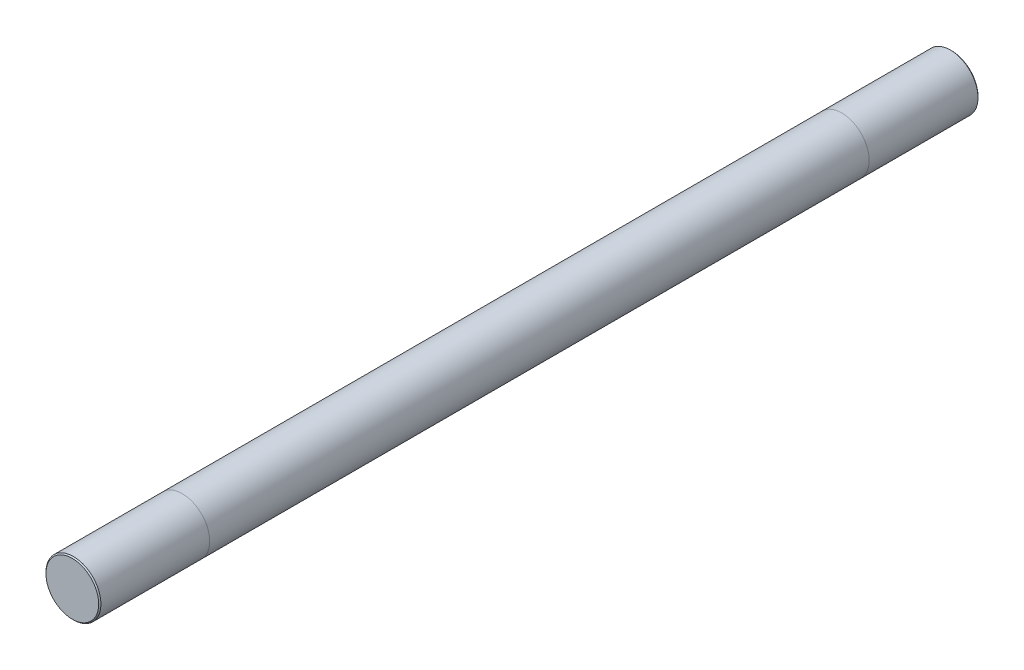
SolidWorks part; units mm, degrees
material "Plain Carbon Steel"
ref_plane "Front Plane" through (0, 0, 0) normal (0, 0, 1) x (1, 0, 0)
ref_plane "Top Plane" through (0, 0, 0) normal (0, 1, 0) x (1, 0, 0)
ref_plane "Right Plane" through (0, 0, 0) normal (1, 0, 0) x (0, 0, -1)
sketch "Sketch1" plane through (0, 0, 0) normal (0, 0, 1) x (1, 0, 0)
  circle A0 centre (0, 0) radius 3.175 construction
  dimension "Diameter" = 6.35
sketch "Sketch2" plane through (0, 0, 0) normal (1, 0, 0) x (0, 0, -1)
  line L0 (50.8, 0) -> (-50.8, 0) construction
  point P0 (-40.64, 0)
  point P3 (0, 0)
  point P4 (40.64, 0)
  point P6 (-35.56, 0)
  point P7 (35.56, 0)
  dimension "Length" = 101.6
  dimension "D1" = 10.16
  dimension "D2" = 10.16
  dimension "D3" = 15.24
  dimension "D4" = 15.24
sketch "Sketch3" plane through (0, 0, 0) normal (0, 0, 1) x (1, 0, 0)
  circle A0 centre (0, 0) radius 3.175 construction
  circle A1 centre (0, 0) radius 3.175
extrude "Boss-Extrude1" add sketch "Sketch3" along normal up to vertex (50.8 mm away) and the other way up to vertex (50.8 mm away) up to point (0, 0, 50.8) other way up to point (0, 0, -50.8)
chamfer "Chamfer1" distance 0.127 angle 45 2 edges at (3.175, 0, 50.8) (3.175, 0, -50.8)
ref_plane "Plane1" through (0, 0, 38.1) normal (0, 0, 1) x (1, 0, 0)
ref_plane "Plane2" through (0, 0, -38.1) normal (0, 0, -1) x (-1, 0, 0)
split line "Split Line1"
equation "\"D1@Chamfer1\"=\"Diameter@Sketch1\"*.02"
equation "\"D1@Sketch2\"=\"D2@Sketch2\""
equation "\"D2@Sketch2\"=\"Length@Sketch2\"*.1"
equation "\"D3@Sketch2\"=\"Length@Sketch2\"*.15"
equation "\"D4@Sketch2\"=\"D3@Sketch2\""
